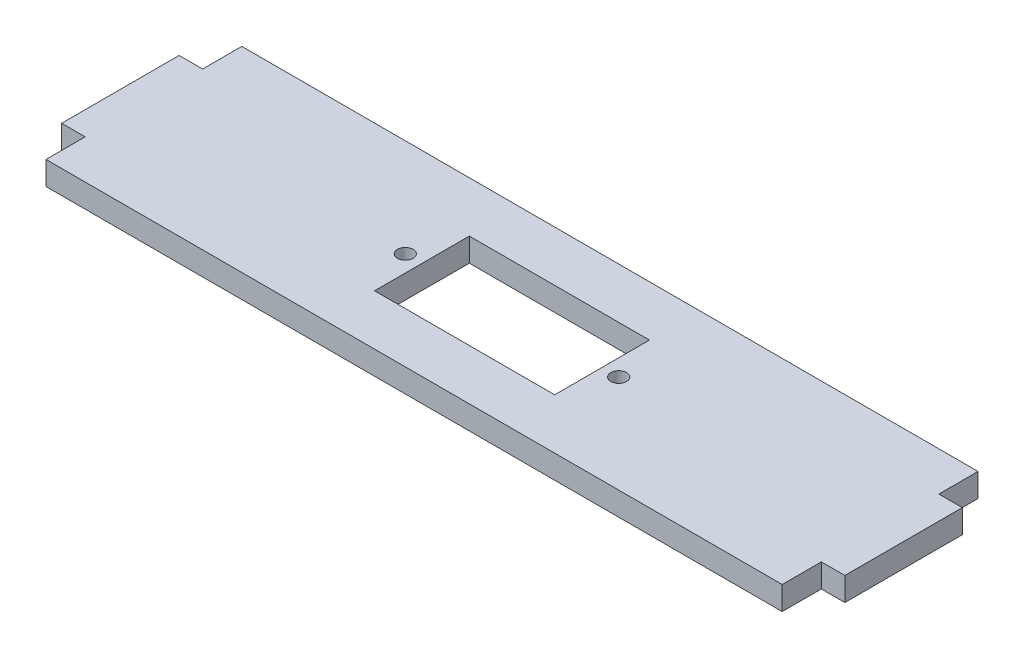
SolidWorks part; units mm, degrees
ref_plane "Front Plane" through (0, 0, 0) normal (0, 0, 1) x (1, 0, 0)
ref_plane "Top Plane" through (0, 0, 0) normal (0, 1, 0) x (1, 0, 0)
ref_plane "Right Plane" through (0, 0, 0) normal (1, 0, 0) x (0, 0, -1)
sketch "Sketch1" plane through (0, 0, 0) normal (0, 1, 0) x (1, 0, 0)
  line L0 (50, -7.5) -> (47, -7.5)
  line L1 (-50, 12.5) -> (50, 12.5)
  line L2 (-50, 12.5) -> (-50, -12.5)
  line L3 (-50, -12.5) -> (50, -12.5)
  line L4 (50, 12.5) -> (50, -12.5)
  line L5 (0, -12.5) -> (0, 12.5) construction
  line L6 (-50, 0) -> (50, 0) construction
  line L7 (50, 12.5) -> (47, 12.5)
  line L8 (50, 12.5) -> (50, 7.5)
  line L9 (50, 7.5) -> (47, 7.5)
  line L10 (47, 12.5) -> (47, 7.5)
  line L11 (-50, 12.5) -> (-47, 12.5)
  line L12 (-50, 12.5) -> (-50, 7.5)
  line L13 (-50, 7.5) -> (-47, 7.5)
  line L14 (-47, 12.5) -> (-47, 7.5)
  line L15 (47, -12.5) -> (47, -7.5)
  line L16 (50, -12.5) -> (47, -12.5)
  line L17 (50, -12.5) -> (50, -7.5)
  line L18 (-50, -7.5) -> (-47, -7.5)
  line L19 (-47, -12.5) -> (-47, -7.5)
  line L20 (-50, -12.5) -> (-47, -12.5)
  line L21 (-50, -12.5) -> (-50, -7.5)
  point P0 (0, 0)
  dimension "D1" = 100
  dimension "D2" = 25
  dimension "D3" = 5
  dimension "D4" = 5
  dimension "D5" = 3
  dimension "D6" = 3
extrude "Boss-Extrude1" add sketch "Sketch1" along normal blind 3 contours L1 L14 L13 L2 L3 L4 L9 L10
sketch "Sketch2" plane through (0, 3, 0) normal (0, 1, 0) x (1, 0, 0)
  line L0 (0, 0) -> (-43.6272, 0) construction
  line L1 (0, 0) -> (24.8866, 0) construction
  line L2 (0, 6.05) -> (0, -6.05) construction
  line L3 (-11.5, -6.05) -> (11.5, -6.05)
  line L4 (-11.5, -6.05) -> (-11.5, 6.05)
  line L5 (-11.5, 6.05) -> (11.5, 6.05)
  line L6 (11.5, -6.05) -> (11.5, 6.05)
  circle A0 centre (-13.625, 0) radius 1
  circle A2 centre (13.625, 0) radius 1
  dimension "D1" = 2
  dimension "D2" = 23
  dimension "D4" = 27.25
  dimension "D3" = 12.1
extrude "Cut-Extrude1" cut sketch "Sketch2" against normal blind 23.3
